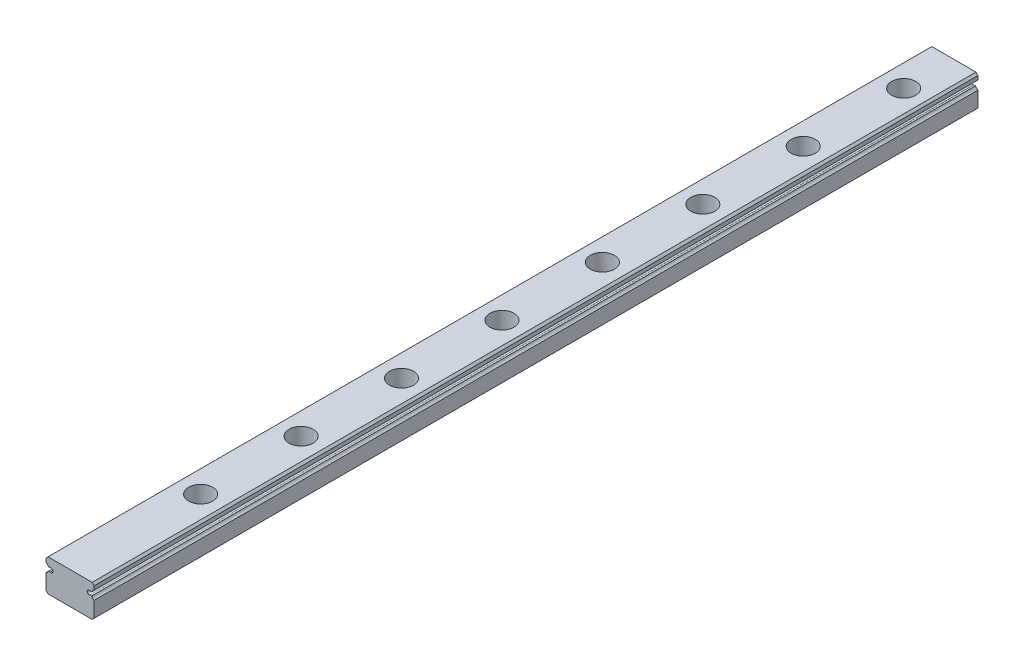
SolidWorks part; units mm, degrees
material "Chrome Stainless Steel"
ref_plane "Front Plane" through (0, 0, 0) normal (0, 0, 1) x (1, 0, 0)
ref_plane "Top Plane" through (0, 0, 0) normal (0, 1, 0) x (1, 0, 0)
ref_plane "Right Plane" through (0, 0, 0) normal (1, 0, 0) x (0, 0, -1)
sketch "Sketch1" plane through (0, 0, 0) normal (0, 0, 1) x (1, 0, 0)
  line L0 (0, 4) -> (0, -4) construction
  line L1 (5.5, -4) -> (-5.5, -4)
  line L2 (-5.5, -4) -> (-6, -3.5)
  line L3 (-6, -3.5) -> (-6, 0.3689)
  line L4 (5.5, 4) -> (-5.5, 4)
  line L5 (-5.5, 4) -> (-6, 3.5)
  line L6 (-6, 2.5511) -> (-6, 3.5)
  line L7 (-5.3839, 0.985) -> (-4.9211, 0.985)
  line L8 (-5.3839, 1.935) -> (-4.9211, 1.935)
  line L9 (5.3839, 0.985) -> (4.9211, 0.985)
  line L10 (5.5, 4) -> (6, 3.5)
  line L11 (6, 2.5511) -> (6, 3.5)
  line L12 (5.3839, 1.935) -> (4.9211, 1.935)
  line L13 (6, -3.5) -> (6, 0.3689)
  line L14 (5.5, -4) -> (6, -3.5)
  circle A0 centre (-6.475, 1.46) radius 1.19 construction
  circle A1 centre (-4.765, 1.46) radius 0.5 construction
  arc A2 (-6, 0.3689) -> (-5.3839, 0.985) centre (-6.475, 1.46) ccw
  arc A3 (-5.3839, 1.935) -> (-6, 2.5511) centre (-6.475, 1.46) ccw
  arc A4 (-4.9211, 0.985) -> (-4.9211, 1.935) centre (-4.765, 1.46) ccw
  arc A5 (5.3839, 1.935) -> (6, 2.5511) centre (6.475, 1.46) cw
  arc A6 (4.9211, 0.985) -> (4.9211, 1.935) centre (4.765, 1.46) cw
  arc A7 (6, 0.3689) -> (5.3839, 0.985) centre (6.475, 1.46) cw
  point P4 (0, 0)
  dimension "D5" = 5.46
  dimension "D6" = 6.475
  dimension "D7" = 2.38
  dimension "D11" = 1
  dimension "D12" = 5.46
  dimension "D13" = 4.765
  dimension "D1" = 8
  dimension "D2" = 0.5
  dimension "D3" = 0.5
  dimension "D4" = 6
  dimension "D8" = 0.5
  dimension "D9" = 0.5
  dimension "D10" = 6
  dimension "D14" = 0.475
  dimension "D15" = 0.475
extrude "Boss-Extrude1" add sketch "Sketch1" along normal blind 220 contours L13 A7 L9 A6 L12 A5 L11 L10 L4 L5 L6 A3 L8 A4 L7 A2 L3 L2 L1 L14
sketch "Sketch2" plane through (0, 4, 0) normal (0, 1, 0) x (1, 0, 0)
  line L0 (5.5, 0) -> (-5.5, 0) construction
  circle A0 centre (0, -12.5) radius 3
  dimension "D1" = 12.5
extrude "Cut-Extrude1" cut sketch "Sketch2" against normal blind 4.5
sketch "Sketch3" plane through (0, -0.5, 0) normal (0, 1, 0) x (1, 0, 0)
  circle A0 centre (0, -12.5) radius 1.75
extrude "Cut-Extrude2" cut sketch "Sketch3" against normal through all
pattern_linear "LPattern1" count 8 spacing 25 along (0, 0, 1) of "Cut-Extrude1", "Cut-Extrude2"
